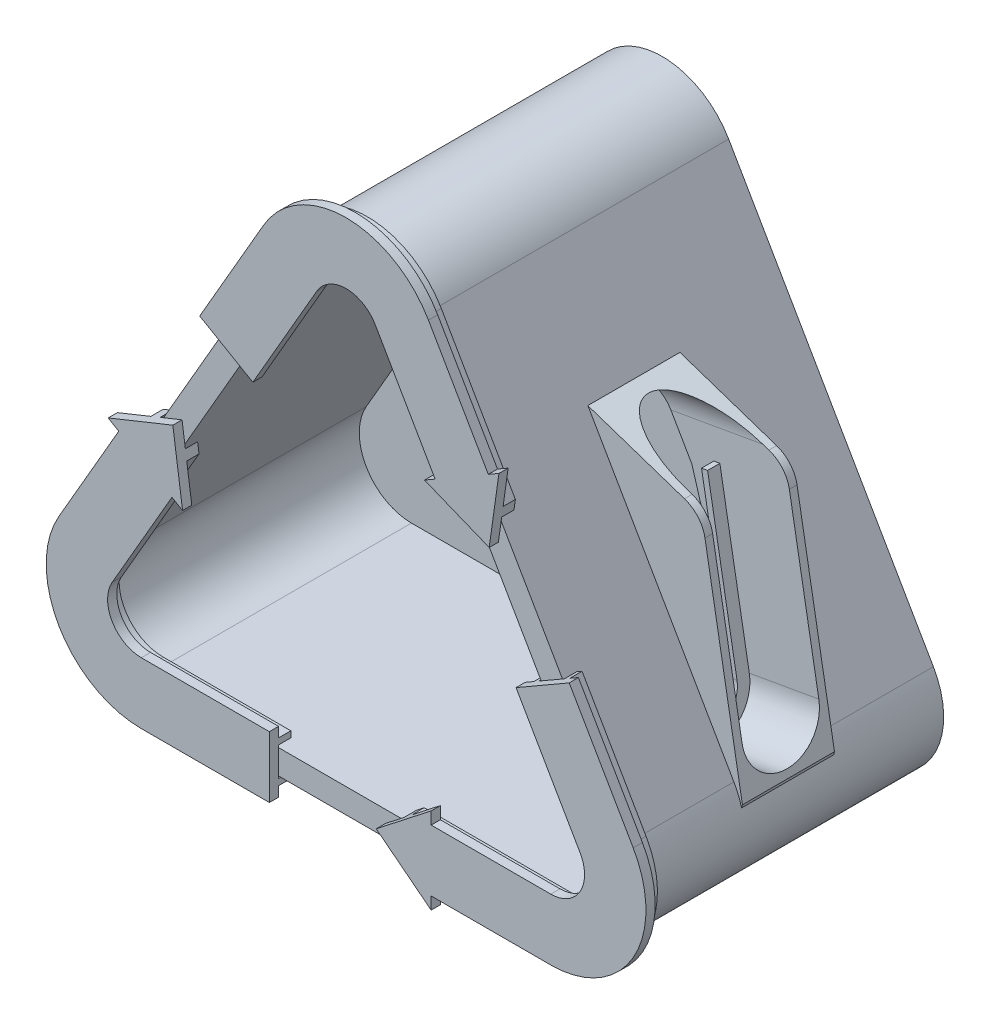
SolidWorks part; units mm, degrees
ref_plane "Front Plane" through (0, 0, 0) normal (0, 0, 1) x (1, 0, 0)
ref_plane "Top Plane" through (0, 0, 0) normal (0, 1, 0) x (1, 0, 0)
ref_plane "Right Plane" through (0, 0, 0) normal (1, 0, 0) x (0, 0, -1)
sketch "Sketch2" plane through (0, 0, 0) normal (0, 0, 1) x (1, 0, 0)
  line L0 (-110, 0) -> (110, 0)
  line L1 (-110, 0) -> (0, 190.5256)
  line L2 (0, 190.5256) -> (110, 0)
  point P4 (0, 0)
  dimension "D1" = 220
extrude "Boss-Extrude1" add sketch "Sketch2" along normal blind 100
fillet "Fillet1" radius 25 3 edges at (-110, 0, 50) (110, 0, 50) (0, 190.5256, 50)
sketch "Sketch3" plane through (0, 0, 100) normal (0, 0, 1) x (1, 0, 0)
  line L6 (-14.7224, 149.0256) -> (-81.4212, 33.5)
  line L7 (-66.6987, 8) -> (66.6987, 8)
  line L8 (81.4212, 33.5) -> (14.7224, 149.0256)
  line L9 (-14.7224, 149.0256) -> (-81.4212, 33.5)
  line L10 (-66.6987, 8) -> (66.6987, 8)
  line L11 (81.4212, 33.5) -> (14.7224, 149.0256)
  arc A6 (-81.4212, 33.5) -> (-66.6987, 8) centre (-66.6987, 25) ccw
  arc A8 (-81.4212, 33.5) -> (-66.6987, 8) centre (-66.6987, 25) ccw
  arc A13 (66.6987, 8) -> (81.4212, 33.5) centre (66.6987, 25) ccw
  arc A15 (66.6987, 8) -> (81.4212, 33.5) centre (66.6987, 25) ccw
  arc A16 (14.7224, 149.0256) -> (-14.7224, 149.0256) centre (0, 140.5256) ccw
  arc A17 (14.7224, 149.0256) -> (-14.7224, 149.0256) centre (0, 140.5256) ccw
  dimension "D1" = 8
extrude "Cut-Extrude1" cut sketch "Sketch3" against normal offset from surface (85 mm away) 15 up to face at (0, 63.5085, 0)
ref_plane "Plane1" through (0, 0, 50) normal (0, 0, 1) x (1, 0, 0)
sketch "Sketch10" plane through (0, 0, 50) normal (0, 0, 1) x (1, 0, 0)
  line L0 (49.9635, 121.622) -> (66.4601, 28.0653) construction
  line L1 (66.4601, 28.0653) -> (91.1295, 32.4152) construction
  line L2 (91.1295, 32.4152) -> (74.6329, 125.9719)
  line L3 (74.6329, 125.9719) -> (49.9635, 121.622) construction
  line L4 (49.9635, 121.622) -> (49.9635, 14.8838) construction
  line L5 (74.6329, 125.9719) -> (37.2701, 125.9719)
  line L6 (88.3494, 37.5) -> (21.6506, 153.0256) construction
  line L7 (66.4601, 28.0653) -> (37.2701, 125.9719)
  line L8 (66.4601, 28.0653) -> (66.4601, 8)
  line L9 (91.1295, 32.4152) -> (84.6994, 8)
  line L10 (84.6994, 8) -> (66.4601, 8)
  line L11 (-66.6987, 8) -> (66.6987, 8) construction
  dimension "D1" = 95
  dimension "D2" = 25.05
  dimension "D3" = 10
extrude "Boss-Extrude3" add sketch "Sketch10" along normal mid plane 30
sketch "Sketch12" plane through (93.9249, 16.5615, 0) normal (0.9848, 0.1736, 0) x (0, 0, -1)
  line L0 (-35, 63.5983) -> (-65, 63.5983) construction
  line L1 (-50, 108.5983) -> (-50, 18.5983) construction
  line L2 (-65, 16.0983) -> (-65, 111.0983) construction
  line L3 (-50, 31.0983) -> (-50, 96.0983) construction
  line L4 (-50, 91.0391) -> (-50, -91.0391) construction
  line L5 (-62.5, 31.0983) -> (-62.5, 96.0983)
  line L6 (-37.5, 31.0983) -> (-37.5, 96.0983)
  line L7 (-65, 111.0983) -> (-35, 111.0983) construction
  line L8 (-61.5, 31.0983) -> (-61.5, 96.0983) construction
  line L9 (-38.5, 31.0983) -> (-38.5, 96.0983) construction
  arc A0 (-62.5, 31.0983) -> (-37.5, 31.0983) centre (-50, 31.0983) ccw
  arc A1 (-37.5, 96.0983) -> (-62.5, 96.0983) centre (-50, 96.0983) ccw
  arc A2 (-38.5, 96.0983) -> (-61.5, 96.0983) centre (-50, 96.0983) ccw construction
  arc A3 (-61.5, 31.0983) -> (-38.5, 31.0983) centre (-50, 31.0983) ccw construction
  point P10 (-50, 63.5983)
  dimension "D2" = 90
  dimension "D3" = 12.5
  dimension "D1" = 47.5
  dimension "D4" = 1
extrude "Cut-Extrude3" cut sketch "Sketch12" against normal up to next
sketch "Sketch14" plane through (0, 0, 65) normal (0, 0, 1) x (1, 0, 0)
  line L0 (77.899, 107.4491) -> (40.7751, 119.9011)
  line L1 (91.1295, 32.4152) -> (74.6329, 125.9719) construction
  line L2 (88.3494, 37.5) -> (21.6506, 153.0256) construction
  line L3 (37.2701, 125.9719) -> (88.3494, 37.5) construction
  line L4 (74.6329, 125.9719) -> (37.2701, 125.9719) construction
  line L5 (37.2701, 125.9719) -> (40.7751, 119.9011)
  line L6 (77.899, 107.4491) -> (74.6329, 125.9719)
  line L7 (74.6329, 125.9719) -> (37.2701, 125.9719)
  line L8 (40.7751, 119.9011) -> (88.3494, 37.5) construction
  line L9 (91.1295, 32.4152) -> (77.899, 107.4491) construction
extrude "Cut-Extrude4" cut sketch "Sketch14" against normal through all
fillet "Fillet2" radius 10 2 edges at (77.899, 107.4491, 36.25) (77.899, 107.4491, 63.75)
sketch "Sketch7" plane through (0, 0, 0) normal (0, -1, 0) x (1, 0, 0)
  line L0 (-66.6987, 100) -> (66.6987, 100) construction
  line L1 (-66.6987, 100) -> (-66.6987, 0) construction
  line L2 (0, 0) -> (0, 173.6429) construction
  line L3 (-66.6987, 50) -> (66.6987, 50) construction
  line L4 (66.6987, 0) -> (66.6987, 100) construction
  circle A0 centre (-51.6987, 85) radius 7.5
  circle A1 centre (51.6987, 85) radius 7.5
  circle A2 centre (51.6987, 15) radius 7.5
  circle A3 centre (-51.6987, 15) radius 7.5
  dimension "D1" = 15
  dimension "D2" = 15
  dimension "D3" = 15
extrude "Cut-Extrude2" cut sketch "Sketch7" against normal blind 2
sketch "Sketch16" plane through (93.9249, 16.5615, 0) normal (0.9848, 0.1736, 0) x (0, 0, -1)
  line L0 (-58.5, 31.0983) -> (-58.5, 86.3453)
  line L1 (-41.5, 86.3453) -> (-41.5, 31.0983)
  line L2 (-62.5, 86.3453) -> (-58.5, 86.3453)
  line L3 (-37.5, 86.3453) -> (-41.5, 86.3453)
  line L7 (-35, 16.0983) -> (-35, 86.3453)
  line L8 (-35, 86.3453) -> (-37.5, 86.3453)
  line L9 (-37.5, 86.3453) -> (-37.5, 31.0983)
  line L10 (-62.5, 31.0983) -> (-62.5, 86.3453)
  line L11 (-35, 86.3453) -> (-37.5, 86.3453)
  line L12 (-65, 86.3453) -> (-65, 16.0983)
  line L13 (-65, 16.0983) -> (-35, 16.0983)
  line L14 (-35, 16.0983) -> (-35, 86.3453)
  line L16 (-37.5, 86.3453) -> (-37.5, 31.0983) construction
  line L17 (-62.5, 31.0983) -> (-62.5, 86.3453) construction
  line L19 (-65, 86.3453) -> (-65, 16.0983)
  line L20 (-65, 16.0983) -> (-35, 16.0983)
  line L25 (-62.5, 86.3453) -> (-65, 86.3453)
  line L26 (-62.5, 86.3453) -> (-65, 86.3453)
  arc A0 (-58.5, 31.0983) -> (-41.5, 31.0983) centre (-50, 31.0983) ccw
  arc A1 (-62.5, 31.0983) -> (-37.5, 31.0983) centre (-50, 31.0983) ccw
  arc A2 (-62.5, 31.0983) -> (-37.5, 31.0983) centre (-50, 31.0983) ccw construction
  dimension "D1" = 0
  dimension "D2" = 4
extrude "Boss-Extrude5" add sketch "Sketch16" along normal blind 2 from offset 25 offset against normal yes
sketch "Sketch6" plane through (0, 0, 100) normal (0, 0, 1) x (1, 0, 0)
  line L0 (46.3377, 122.2663) -> (26.8468, 156.0256)
  line L1 (-26.8468, 156.0256) -> (-47.6962, 119.9134)
  line L2 (46.6255, 101.7678) -> (49.8018, 124.2663)
  line L3 (-21.6506, 153.0256) -> (-88.3494, 37.5)
  line L4 (-66.6987, 0) -> (66.6987, 0)
  line L5 (88.3494, 37.5) -> (21.6506, 153.0256)
  line L6 (-21.6506, 153.0256) -> (-42.5, 116.9134)
  line L8 (47.533, 108.1959) -> (21.6506, 153.0256)
  line L9 (49.8018, 124.2663) -> (46.3377, 122.2663)
  line L10 (-47.6962, 119.9134) -> (-30.3756, 109.9134)
  line L11 (-14.7224, 149.0256) -> (-81.4212, 33.5) construction
  line L12 (-76.225, 30.5) -> (-9.5263, 146.0256)
  line L13 (9.5263, 146.0256) -> (76.225, 30.5)
  line L14 (-30.3756, 109.9134) -> (-9.5263, 146.0256)
  line L15 (9.5263, 146.0256) -> (29.0172, 112.2663)
  line L16 (0, 140.5256) -> (0, 56.7677) construction
  line L17 (50.0896, 103.7678) -> (43.1614, 99.7678) construction
  line L18 (25.5531, 110.2663) -> (46.6255, 101.7678)
  line L19 (-26.8468, 156.0256) -> (-93.5455, 40.5) construction
  line L20 (-21.6506, 153.0256) -> (-88.3494, 37.5) construction
  line L21 (88.3494, 37.5) -> (21.6506, 153.0256) construction
  line L22 (93.5455, 40.5) -> (26.8468, 156.0256) construction
  line L23 (29.0172, 112.2663) -> (25.5531, 110.2663)
  line L26 (14.7224, 149.0256) -> (81.4212, 33.5) construction
  line L27 (88.3494, 37.5) -> (21.6506, 153.0256) construction
  arc A0 (26.8468, 156.0256) -> (-26.8468, 156.0256) centre (0, 140.5256) ccw
  arc A2 (9.5263, 146.0256) -> (-9.5263, 146.0256) centre (0, 140.5256) ccw
  arc A3 (-88.3494, 37.5) -> (-66.6987, 0) centre (-66.6987, 25) ccw
  arc A4 (66.6987, 0) -> (88.3494, 37.5) centre (66.6987, 25) ccw
  arc A5 (21.6506, 153.0256) -> (-21.6506, 153.0256) centre (0, 140.5256) ccw
  arc A8 (21.6506, 153.0256) -> (-21.6506, 153.0256) centre (0, 140.5256) ccw
  arc A9 (9.5263, 146.0256) -> (-9.5263, 146.0256) centre (0, 140.5256) ccw
  point P19 (-48.0718, 91.2628)
  point P63 (46.6255, 101.7678)
  line M12 (-81.4212, 33.5) -> (-14.7224, 149.0256)
  arc M13 (-14.7224, 149.0256) -> (14.7224, 149.0256) centre (0, 140.5256) cw
  line M14 (14.7224, 149.0256) -> (81.4212, 33.5)
  line M17 (-21.6506, 153.0256) -> (-88.3494, 37.5)
  line M21 (88.3494, 37.5) -> (21.6506, 153.0256)
  arc M22 (21.6506, 153.0256) -> (-21.6506, 153.0256) centre (0, 140.5256) ccw
  dimension "D4" = 25
  dimension "D5" = 28
  dimension "D2" = 6
  dimension "D3" = 6
extrude "Boss-Extrude2" add sketch "Sketch6" along normal blind 3 separate body contours L0 A0 L1 L10 L2 L9 M17 M22 M21 | L18 L2 L10 M14 M21 M22 M17 M12 M13 | A9 L15 L23 L18 L10 L14 M14 M13 M12
sketch "Sketch19" plane through (0, 0, 100) normal (0, 0, -1) x (-1, 0, 0)
  line L0 (-81.4212, 33.5) -> (-14.7224, 149.0256) construction
  line L1 (14.7224, 149.0256) -> (81.4212, 33.5) construction
  line L2 (-40.6048, 104.1959) -> (-14.7224, 149.0256) construction
  line L3 (88.3494, 37.5) -> (21.6506, 153.0256)
  line L4 (-66.6987, 0) -> (66.6987, 0)
  line L5 (-21.6506, 153.0256) -> (-88.3494, 37.5)
  line L9 (14.7224, 149.0256) -> (35.5718, 112.9134) construction
  line L10 (43.1495, 117.2884) -> (22.3002, 153.4006)
  line L11 (-22.3002, 153.4006) -> (-47.7032, 109.4012)
  line L12 (44.8816, 118.2884) -> (24.0322, 154.4006)
  line L13 (-24.0322, 154.4006) -> (-48.157, 112.6153)
  line L14 (-24.0322, 154.4006) -> (-90.7309, 38.875) construction
  line L15 (-22.3002, 153.4006) -> (-88.9989, 37.875) construction
  line L16 (-21.6506, 153.0256) -> (-88.3494, 37.5) construction
  line L17 (88.3494, 37.5) -> (21.6506, 153.0256) construction
  line L18 (88.9989, 37.875) -> (22.3002, 153.4006) construction
  line L19 (90.7309, 38.875) -> (24.0322, 154.4006) construction
  line L20 (43.1495, 117.2884) -> (44.8816, 118.2884)
  line L21 (-25.5531, 110.2663) -> (-46.6255, 101.7678) construction
  line L22 (-36.4656, 105.8653) -> (-39.476, 104.6512)
  line L23 (-25.5531, 110.2663) -> (-29.0172, 112.2663)
  line L24 (-29.0172, 112.2663) -> (-9.5263, 146.0256)
  line L25 (9.5263, 146.0256) -> (30.3756, 109.9134)
  line L26 (30.3756, 109.9134) -> (47.6962, 119.9134)
  line L27 (47.6962, 119.9134) -> (26.8468, 156.0256)
  line L28 (-26.8468, 156.0256) -> (-46.3377, 122.2663)
  line L29 (-46.3377, 122.2663) -> (-49.8018, 124.2663)
  line L30 (-49.8018, 124.2663) -> (-46.6255, 101.7678)
  line L31 (-46.6255, 101.7678) -> (-25.5531, 110.2663)
  line L39 (-48.157, 112.6153) -> (-47.7032, 109.4012)
  line L40 (47.6962, 119.9134) -> (30.3756, 109.9134) construction
  line L41 (44.8816, 118.2884) -> (43.1495, 117.2884)
  line L42 (34.9223, 112.5384) -> (33.1902, 111.5384)
  line L43 (-39.476, 104.6512) -> (-14.0729, 148.6506)
  line L44 (14.0729, 148.6506) -> (34.9223, 112.5384)
  line L45 (-36.4656, 105.8653) -> (-12.3409, 147.6506)
  line L46 (12.3409, 147.6506) -> (33.1902, 111.5384)
  line L47 (-81.4212, 33.5) -> (-40.6048, 104.1959) construction
  line L48 (-81.4212, 33.5) -> (-14.7224, 149.0256) construction
  line L49 (-80.7716, 33.125) -> (-39.476, 104.6512) construction
  line L50 (-80.7716, 33.125) -> (-14.0729, 148.6506) construction
  line L51 (-79.0396, 32.125) -> (-36.4656, 105.8653) construction
  line L52 (-79.0396, 32.125) -> (-12.3409, 147.6506) construction
  line L53 (-40.6048, 104.1959) -> (-46.6255, 101.7678) construction
  line L54 (-25.5531, 110.2663) -> (-36.4656, 105.8653) construction
  line L55 (35.5718, 112.9134) -> (34.9223, 112.5384) construction
  line L56 (33.1902, 111.5384) -> (30.3756, 109.9134) construction
  line L57 (-39.476, 104.6512) -> (-40.6048, 104.1959) construction
  arc A0 (14.7224, 149.0256) -> (-14.7224, 149.0256) centre (0, 140.5256) ccw construction
  arc A1 (14.7224, 149.0256) -> (-14.7224, 149.0256) centre (0, 140.5256) ccw construction
  arc A2 (22.3002, 153.4006) -> (-22.3002, 153.4006) centre (0, 140.5256) ccw
  arc A3 (66.6987, 0) -> (88.3494, 37.5) centre (66.6987, 25) ccw
  arc A4 (-88.3494, 37.5) -> (-66.6987, 0) centre (-66.6987, 25) ccw
  arc A5 (21.6506, 153.0256) -> (-21.6506, 153.0256) centre (0, 140.5256) ccw
  arc A8 (21.6506, 153.0256) -> (-21.6506, 153.0256) centre (0, 140.5256) ccw construction
  arc A9 (24.0322, 154.4006) -> (-24.0322, 154.4006) centre (0, 140.5256) ccw
  arc A10 (14.0729, 148.6506) -> (-14.0729, 148.6506) centre (0, 140.5256) ccw
  arc A11 (12.3409, 147.6506) -> (-12.3409, 147.6506) centre (0, 140.5256) ccw
  arc A12 (9.5263, 146.0256) -> (-9.5263, 146.0256) centre (0, 140.5256) ccw
  arc A13 (26.8468, 156.0256) -> (-26.8468, 156.0256) centre (0, 140.5256) ccw
  line M33 (30.3756, 109.9134) -> (47.6962, 119.9134)
  line M38 (-49.8018, 124.2663) -> (-46.6255, 101.7678)
  line M39 (-46.6255, 101.7678) -> (-25.5531, 110.2663)
  dimension "D1" = 0
  dimension "D2" = 0.75
  dimension "D3" = 2
  dimension "D4" = 0
  dimension "D5" = 0.75
  dimension "D6" = 2
extrude "Boss-Extrude6" add sketch "Sketch19" along normal blind 4 contours L12 A9 L13 L11 A2 L10 M38 M33 | A11 L46 L44 A10 L43 L45 M33 M39
pattern_circular "CirPattern2" count 3 over 360 about axis through (0, 63.5085, 0) along (0, 0, 1) of bodies 116 103
pattern_circular "CirPattern3" [suppressed] count 2 over 360
sketch "Sketch18" plane through (0, 0, 0) normal (0, 0, -1) x (-1, 0, 0)
  line L0 (-5612.026, 3175.9914) -> (-5462.026, 3175.9914) construction
  line L1 (-42.8254, 65.7682) -> (42.1746, 65.7682) construction
  line L2 (21.1072, 154.4992) -> (106.1072, 154.4992) construction
  line L3 (-37.9196, 65.1258) -> (-31.7582, 53.4633)
  line L4 (-31.7582, 53.4633) -> (-32.9685, 47.0819)
  line L5 (-32.9685, 47.0819) -> (-26.9171, 44.8814)
  line L6 (-26.9171, 44.8814) -> (-21.6706, 51.5501)
  line L7 (-21.6706, 51.5501) -> (-21.6706, 48.9523)
  line L8 (-21.6706, 48.9523) -> (-15.7075, 37.6649)
  line L9 (-15.7075, 37.6649) -> (-10.1554, 33.2969)
  line L10 (-10.1554, 33.2969) -> (-4.8527, 33.9299)
  line L11 (-4.8527, 33.9299) -> (0, 33.0095)
  line L12 (0, 33.0095) -> (3.6746, 34.9508)
  line L13 (3.6746, 34.9508) -> (9.3178, 33.2091)
  line L14 (9.3178, 33.2091) -> (13.614, 37.0204)
  line L15 (13.614, 37.0204) -> (20.6317, 49.6775)
  line L16 (20.6317, 49.6775) -> (20.6317, 51.5501)
  line L17 (20.6317, 51.5501) -> (25.0179, 45.4167)
  line L18 (25.0179, 45.4167) -> (27.2736, 45.4167)
  line L19 (27.2736, 45.4167) -> (31.6597, 47.0819)
  line L20 (31.6597, 47.0819) -> (30.898, 53.4633)
  line L21 (30.898, 53.4633) -> (37.3644, 65.1258)
  line L22 (37.3644, 65.1258) -> (23.6463, 82.7336)
  line L23 (23.6463, 82.7336) -> (14.2717, 84.5115)
  line L24 (14.2717, 84.5115) -> (10.141, 87.7613)
  line L25 (10.141, 87.7613) -> (-0.4718, 86.8579)
  line L26 (-0.4718, 86.8579) -> (-10.9015, 87.3096)
  line L27 (-10.9015, 87.3096) -> (-15.7075, 84.7706)
  line L28 (-15.7075, 84.7706) -> (-24.7648, 82.7336)
  line L29 (-24.7648, 82.7336) -> (-37.9196, 65.1258)
  line L30 (-12.9315, 68.6436) -> (-16.4577, 64.1615)
  line L31 (-16.4577, 64.1615) -> (-14.8204, 62.06)
  line L32 (-14.8204, 62.06) -> (-10.4118, 61.2239)
  line L33 (-10.4118, 61.2239) -> (-7.7649, 62.06)
  line L34 (-7.7649, 62.06) -> (-9.2332, 66.7082)
  line L35 (-9.2332, 66.7082) -> (-12.9315, 68.6436)
  line L36 (8.1998, 66.7082) -> (6.7652, 62.06)
  line L37 (6.7652, 62.06) -> (9.4742, 61.2239)
  line L38 (9.4742, 61.2239) -> (13.8983, 62.2189)
  line L39 (13.8983, 62.2189) -> (15.6017, 64.3841)
  line L40 (15.6017, 64.3841) -> (11.8229, 68.6436)
  line L41 (11.8229, 68.6436) -> (8.1998, 66.7082)
  line L42 (4.382, 50.6138) -> (-5.6867, 50.6138)
  line L43 (-5.6867, 50.6138) -> (-6.3565, 47.0819)
  line L44 (-6.3565, 47.0819) -> (-0.3052, 44.8814)
  line L45 (-0.3052, 44.8814) -> (5.6902, 47.1575)
  line L46 (5.6902, 47.1575) -> (4.382, 50.6138)
  dimension "D1" = 150
  dimension "D2" = 85
  dimension "D3" = 85
extrude "Cut-Extrude5" cut sketch "Sketch18" against normal blind 1.5 contours L29 L3 L4 L5 L6 L7 L8 L9 L10 L11 L12 L13 L14 L15 L16 L17 L18 L19 L20 L21 L22 L23 L24 L25 L26 L27 L28
equation "\"SIDE_LENGTH\"=220"
equation "\"D1@Sketch2\"=\"SIDE_LENGTH\""
equation "\"DEPTH\"= 100"
equation "\"D1@Boss-Extrude1\"=\"DEPTH\""
equation "\"SPACE\"=25"
equation "\"D4@Sketch6\"=\"SPACE\""
equation "\"WIDTH\"= 8"
equation "\"D1@Sketch3\"=\"WIDTH\""
equation "\"ARROW_WIDTH\"= 20"
equation "\"D2@Sketch6\"=(\"ARROW_WIDTH\"-\"WIDTH\")/2"
equation "\"D3@Sketch6\"=(\"ARROW_WIDTH\"-\"WIDTH\")/2"
equation "\"FOOT_DIAM\"= 15"
equation "\"D1@Sketch7\"=\"FOOT_DIAM\""
equation "\"FOOT_DEPTH\"=2"
equation "\"D1@Cut-Extrude2\"=\"FOOT_DEPTH\""
